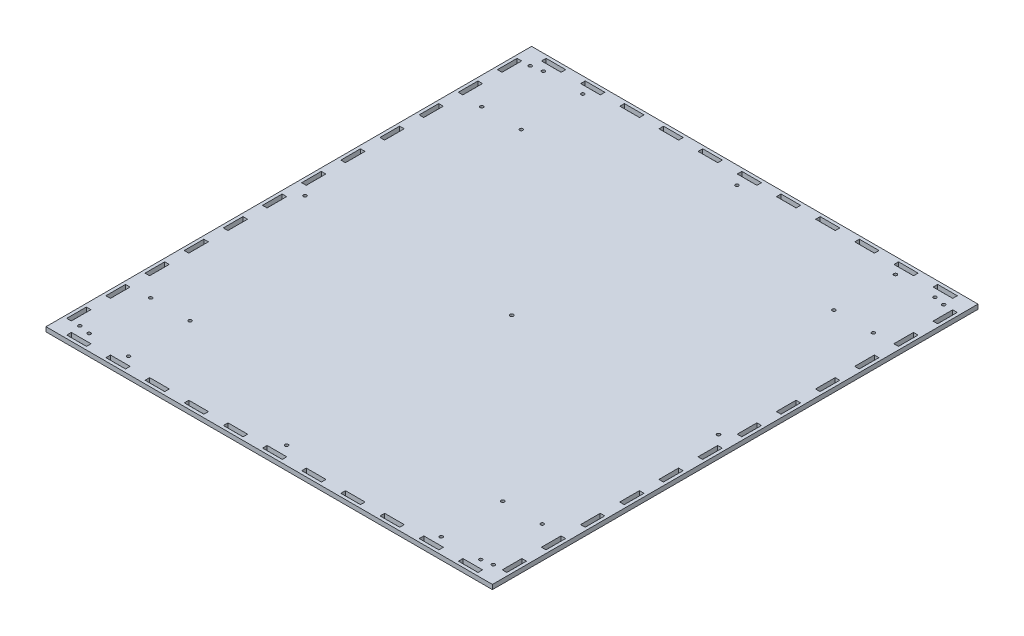
SolidWorks part; units mm, degrees
ref_plane "Спереди" through (0, 0, 0) normal (0, 0, 1) x (1, 0, 0)
ref_plane "Сверху" through (0, 0, 0) normal (0, 1, 0) x (1, 0, 0)
ref_plane "Справа" through (0, 0, 0) normal (1, 0, 0) x (0, 0, -1)
other "Configuration Table"
sketch "Sketch1" plane through (0, 0, 0) normal (0, 1, 0) x (1, 0, 0)
  line L0 (0, 0) -> (0, 290) construction
  line L1 (-285, -310) -> (285, -310)
  line L2 (-285, -310) -> (-285, 310)
  line L3 (-285, 310) -> (285, 310)
  line L4 (285, -310) -> (285, 310)
  line L5 (-285, -310) -> (285, 310) construction
  line L6 (-285, 310) -> (285, -310) construction
  line L7 (0, 290) -> (250, 290) construction
  line L8 (0, 0) -> (285, 0) construction
  line L9 (-212.5, 306) -> (-212.5, 300.15)
  line L10 (-262.5, 306) -> (-237.4, 306)
  line L11 (-262.5, 306) -> (-262.5, 300.15)
  line L12 (-262.5, 300.15) -> (-237.4, 300.15)
  line L13 (-237.4, 306) -> (-237.4, 300.15)
  line L14 (-212.5, 306) -> (-187.4, 306)
  line L15 (-187.4, 306) -> (-187.4, 300.15)
  line L16 (-212.5, 300.15) -> (-187.4, 300.15)
  line L17 (-162.5, 306) -> (-162.5, 300.15)
  line L18 (-162.5, 306) -> (-137.4, 306)
  line L19 (-137.4, 306) -> (-137.4, 300.15)
  line L20 (-162.5, 300.15) -> (-137.4, 300.15)
  line L21 (-112.5, 306) -> (-112.5, 300.15)
  line L22 (-112.5, 306) -> (-87.4, 306)
  line L23 (-87.4, 306) -> (-87.4, 300.15)
  line L24 (-112.5, 300.15) -> (-87.4, 300.15)
  line L25 (-62.5, 306) -> (-62.5, 300.15)
  line L26 (-62.5, 306) -> (-37.4, 306)
  line L27 (-37.4, 306) -> (-37.4, 300.15)
  line L28 (-62.5, 300.15) -> (-37.4, 300.15)
  line L29 (-12.5, 306) -> (-12.5, 300.15)
  line L30 (-12.5, 306) -> (12.6, 306)
  line L31 (12.6, 306) -> (12.6, 300.15)
  line L32 (-12.5, 300.15) -> (12.6, 300.15)
  line L33 (37.5, 306) -> (37.5, 300.15)
  line L34 (37.5, 306) -> (62.6, 306)
  line L35 (62.6, 306) -> (62.6, 300.15)
  line L36 (37.5, 300.15) -> (62.6, 300.15)
  line L37 (87.5, 306) -> (87.5, 300.15)
  line L38 (87.5, 306) -> (112.6, 306)
  line L39 (112.6, 306) -> (112.6, 300.15)
  line L40 (87.5, 300.15) -> (112.6, 300.15)
  line L41 (137.5, 306) -> (137.5, 300.15)
  line L42 (137.5, 306) -> (162.6, 306)
  line L43 (162.6, 306) -> (162.6, 300.15)
  line L44 (137.5, 300.15) -> (162.6, 300.15)
  line L45 (187.5, 306) -> (187.5, 300.15)
  line L46 (187.5, 306) -> (212.6, 306)
  line L47 (212.6, 306) -> (212.6, 300.15)
  line L48 (187.5, 300.15) -> (212.6, 300.15)
  line L49 (237.5, 306) -> (237.5, 300.15)
  line L50 (237.5, 306) -> (262.6, 306)
  line L51 (262.6, 306) -> (262.6, 300.15)
  line L52 (237.5, 300.15) -> (262.6, 300.15)
  line L53 (237.5, -300.15) -> (262.6, -300.15)
  line L54 (262.6, -306) -> (262.6, -300.15)
  line L55 (237.5, -306) -> (262.6, -306)
  line L56 (237.5, -306) -> (237.5, -300.15)
  line L57 (187.5, -300.15) -> (212.6, -300.15)
  line L58 (212.6, -306) -> (212.6, -300.15)
  line L59 (187.5, -306) -> (212.6, -306)
  line L60 (187.5, -306) -> (187.5, -300.15)
  line L61 (137.5, -300.15) -> (162.6, -300.15)
  line L62 (162.6, -306) -> (162.6, -300.15)
  line L63 (137.5, -306) -> (162.6, -306)
  line L64 (137.5, -306) -> (137.5, -300.15)
  line L65 (87.5, -300.15) -> (112.6, -300.15)
  line L66 (112.6, -306) -> (112.6, -300.15)
  line L67 (87.5, -306) -> (112.6, -306)
  line L68 (87.5, -306) -> (87.5, -300.15)
  line L69 (37.5, -300.15) -> (62.6, -300.15)
  line L70 (62.6, -306) -> (62.6, -300.15)
  line L71 (37.5, -306) -> (62.6, -306)
  line L72 (37.5, -306) -> (37.5, -300.15)
  line L73 (-12.5, -300.15) -> (12.6, -300.15)
  line L74 (12.6, -306) -> (12.6, -300.15)
  line L75 (-12.5, -306) -> (12.6, -306)
  line L76 (-12.5, -306) -> (-12.5, -300.15)
  line L77 (-62.5, -300.15) -> (-37.4, -300.15)
  line L78 (-37.4, -306) -> (-37.4, -300.15)
  line L79 (-62.5, -306) -> (-37.4, -306)
  line L80 (-62.5, -306) -> (-62.5, -300.15)
  line L81 (-112.5, -300.15) -> (-87.4, -300.15)
  line L82 (-87.4, -306) -> (-87.4, -300.15)
  line L83 (-112.5, -306) -> (-87.4, -306)
  line L84 (-112.5, -306) -> (-112.5, -300.15)
  line L85 (-162.5, -300.15) -> (-137.4, -300.15)
  line L86 (-137.4, -306) -> (-137.4, -300.15)
  line L87 (-162.5, -306) -> (-137.4, -306)
  line L88 (-162.5, -306) -> (-162.5, -300.15)
  line L89 (-212.5, -300.15) -> (-187.4, -300.15)
  line L90 (-187.4, -306) -> (-187.4, -300.15)
  line L91 (-212.5, -306) -> (-187.4, -306)
  line L92 (-237.4, -306) -> (-237.4, -300.15)
  line L93 (-262.5, -300.15) -> (-237.4, -300.15)
  line L94 (-262.5, -306) -> (-262.5, -300.15)
  line L95 (-262.5, -306) -> (-237.4, -306)
  line L96 (-212.5, -306) -> (-212.5, -300.15)
  line L97 (-281, 237.5) -> (-281, 212.4)
  line L98 (-281, 287.5) -> (-275.15, 287.5)
  line L99 (-281, 287.5) -> (-281, 262.4)
  line L100 (-281, 262.4) -> (-275.15, 262.4)
  line L101 (-275.15, 287.5) -> (-275.15, 262.4)
  line L102 (-281, 237.5) -> (-275.15, 237.5)
  line L103 (-275.15, 237.5) -> (-275.15, 212.4)
  line L104 (-281, 212.4) -> (-275.15, 212.4)
  line L105 (-281, 187.5) -> (-281, 162.4)
  line L106 (-281, 187.5) -> (-275.15, 187.5)
  line L107 (-275.15, 187.5) -> (-275.15, 162.4)
  line L108 (-281, 162.4) -> (-275.15, 162.4)
  line L109 (-281, 137.5) -> (-281, 112.4)
  line L110 (-281, 137.5) -> (-275.15, 137.5)
  line L111 (-275.15, 137.5) -> (-275.15, 112.4)
  line L112 (-281, 112.4) -> (-275.15, 112.4)
  line L113 (-281, 87.5) -> (-281, 62.4)
  line L114 (-281, 87.5) -> (-275.15, 87.5)
  line L115 (-275.15, 87.5) -> (-275.15, 62.4)
  line L116 (-281, 62.4) -> (-275.15, 62.4)
  line L117 (-281, 37.5) -> (-281, 12.4)
  line L118 (-281, 37.5) -> (-275.15, 37.5)
  line L119 (-275.15, 37.5) -> (-275.15, 12.4)
  line L120 (-281, 12.4) -> (-275.15, 12.4)
  line L121 (-281, -12.5) -> (-281, -37.6)
  line L122 (-281, -12.5) -> (-275.15, -12.5)
  line L123 (-275.15, -12.5) -> (-275.15, -37.6)
  line L124 (-281, -37.6) -> (-275.15, -37.6)
  line L125 (-281, -62.5) -> (-281, -87.6)
  line L126 (-281, -62.5) -> (-275.15, -62.5)
  line L127 (-275.15, -62.5) -> (-275.15, -87.6)
  line L128 (-281, -87.6) -> (-275.15, -87.6)
  line L129 (-281, -112.5) -> (-281, -137.6)
  line L130 (-281, -112.5) -> (-275.15, -112.5)
  line L131 (-275.15, -112.5) -> (-275.15, -137.6)
  line L132 (-281, -137.6) -> (-275.15, -137.6)
  line L133 (-281, -162.5) -> (-281, -187.6)
  line L134 (-281, -162.5) -> (-275.15, -162.5)
  line L135 (-275.15, -162.5) -> (-275.15, -187.6)
  line L136 (-281, -187.6) -> (-275.15, -187.6)
  line L137 (-281, -212.5) -> (-281, -237.6)
  line L138 (-281, -212.5) -> (-275.15, -212.5)
  line L139 (-275.15, -212.5) -> (-275.15, -237.6)
  line L140 (-281, -237.6) -> (-275.15, -237.6)
  line L141 (-281, -262.5) -> (-281, -287.6)
  line L142 (-281, -262.5) -> (-275.15, -262.5)
  line L143 (-275.15, -262.5) -> (-275.15, -287.6)
  line L144 (-281, -287.6) -> (-275.15, -287.6)
  line L145 (281, -287.6) -> (275.15, -287.6)
  line L146 (275.15, -262.5) -> (275.15, -287.6)
  line L147 (281, -262.5) -> (275.15, -262.5)
  line L148 (281, -262.5) -> (281, -287.6)
  line L149 (281, -237.6) -> (275.15, -237.6)
  line L150 (275.15, -212.5) -> (275.15, -237.6)
  line L151 (281, -212.5) -> (275.15, -212.5)
  line L152 (281, -212.5) -> (281, -237.6)
  line L153 (281, -187.6) -> (275.15, -187.6)
  line L154 (275.15, -162.5) -> (275.15, -187.6)
  line L155 (281, -162.5) -> (275.15, -162.5)
  line L156 (281, -162.5) -> (281, -187.6)
  line L157 (281, -137.6) -> (275.15, -137.6)
  line L158 (275.15, -112.5) -> (275.15, -137.6)
  line L159 (281, -112.5) -> (275.15, -112.5)
  line L160 (281, -112.5) -> (281, -137.6)
  line L161 (281, -87.6) -> (275.15, -87.6)
  line L162 (275.15, -62.5) -> (275.15, -87.6)
  line L163 (281, -62.5) -> (275.15, -62.5)
  line L164 (281, -62.5) -> (281, -87.6)
  line L165 (281, -37.6) -> (275.15, -37.6)
  line L166 (275.15, -12.5) -> (275.15, -37.6)
  line L167 (281, -12.5) -> (275.15, -12.5)
  line L168 (281, -12.5) -> (281, -37.6)
  line L169 (281, 12.4) -> (275.15, 12.4)
  line L170 (275.15, 37.5) -> (275.15, 12.4)
  line L171 (281, 37.5) -> (275.15, 37.5)
  line L172 (281, 37.5) -> (281, 12.4)
  line L173 (281, 62.4) -> (275.15, 62.4)
  line L174 (275.15, 87.5) -> (275.15, 62.4)
  line L175 (281, 87.5) -> (275.15, 87.5)
  line L176 (281, 87.5) -> (281, 62.4)
  line L177 (281, 112.4) -> (275.15, 112.4)
  line L178 (275.15, 137.5) -> (275.15, 112.4)
  line L179 (281, 137.5) -> (275.15, 137.5)
  line L180 (281, 137.5) -> (281, 112.4)
  line L181 (281, 162.4) -> (275.15, 162.4)
  line L182 (275.15, 187.5) -> (275.15, 162.4)
  line L183 (281, 187.5) -> (275.15, 187.5)
  line L184 (281, 187.5) -> (281, 162.4)
  line L185 (281, 212.4) -> (275.15, 212.4)
  line L186 (275.15, 237.5) -> (275.15, 212.4)
  line L187 (281, 237.5) -> (275.15, 237.5)
  line L188 (275.15, 287.5) -> (275.15, 262.4)
  line L189 (281, 262.4) -> (275.15, 262.4)
  line L190 (281, 287.5) -> (281, 262.4)
  line L191 (281, 287.5) -> (275.15, 287.5)
  line L192 (281, 237.5) -> (281, 212.4)
  line L193 (250, -290) -> (250, -211.4) construction
  line L194 (250, -250.7) -> (178.0385, -250.7) construction
  circle A0 centre (250, 290) radius 2.05
  circle A1 centre (250, -290) radius 2.05
  circle A2 centre (-250, -290) radius 2.05
  circle A3 centre (-250, 290) radius 2.05
  circle A4 centre (-264.3145, -287.5) radius 2.1
  circle A5 centre (-0.3145, -287.5) radius 2.1
  circle A6 centre (263.6855, -287.5) radius 2.1
  circle A7 centre (-0.3145, 0) radius 2.1
  circle A8 centre (263.6855, 0) radius 2.1
  circle A9 centre (-0.3145, 287.5) radius 2.1
  circle A10 centre (263.6855, 287.5) radius 2.1
  circle A11 centre (-264.3145, 0) radius 2.1
  circle A12 centre (-264.3145, 287.5) radius 2.1
  circle A13 centre (-199.6, -290) radius 2.05
  circle A14 centre (-199.6, -211.4) radius 2.05
  circle A16 centre (-250, -211.4) radius 2.05
  circle A17 centre (199.6, -290) radius 2.05
  circle A18 centre (250, -211.4) radius 2.05
  circle A19 centre (199.6, -211.4) radius 2.05
  circle A20 centre (-250, 211.4) radius 2.05
  circle A21 centre (-199.6, 211.4) radius 2.05
  circle A22 centre (-199.6, 290) radius 2.05
  circle A23 centre (199.6, 290) radius 2.05
  circle A24 centre (250, 211.4) radius 2.05
  circle A25 centre (199.6, 211.4) radius 2.05
  point P0 (0, 0)
  dimension "D5" = 4.1
  dimension "D17" = 4.2
  dimension "D20" = 50.4
  dimension "D22" = 78.6
  dimension "D1" = 570
  dimension "D2" = 620
  dimension "D3" = 20
  dimension "D4" = 250
  dimension "D6" = 22.5
  dimension "D7" = 25.1
  dimension "D8" = 4
  dimension "D9" = 5.85
  dimension "D11" = 25.1
  dimension "D12" = 5.85
  dimension "D13" = 22.5
  dimension "D14" = 4
  dimension "D16" = 22.5
  dimension "D23" = 50.4
  dimension "D10" = 11
  dimension "D15" = 12
  dimension "D18" = 3
  dimension "D19" = 3
extrude "Boss-Extrude1" add sketch "Sketch1" along normal blind 5.8
